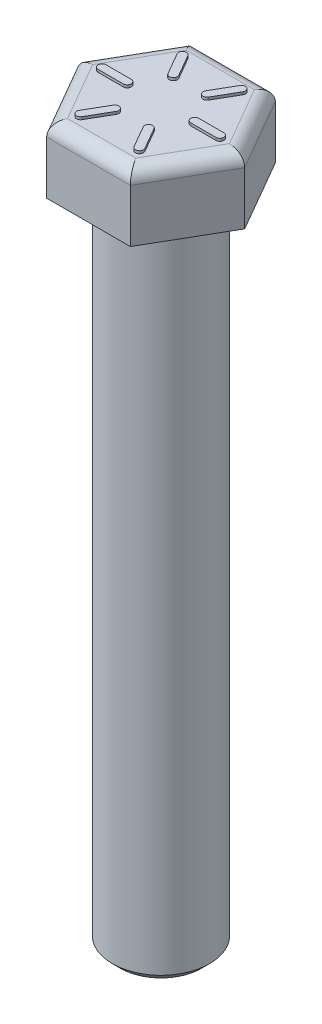
SolidWorks part; units mm, degrees
material "AISI 1045 Steel, cold drawn"
ref_plane "Front" through (0, 0, 0) normal (0, 0, 1) x (1, 0, 0)
ref_plane "Top" through (0, 0, 0) normal (0, 1, 0) x (1, 0, 0)
ref_plane "Right" through (0, 0, 0) normal (1, 0, 0) x (0, 0, -1)
sketch "Sketch1" plane through (0, 0, 0) normal (0, 1, 0) x (1, 0, 0)
  circle A0 centre (0, 0) radius 4.6609
  dimension "D1" = 9.3218
extrude "Boss-Extrude1" add sketch "Sketch1" against normal blind 63.5
cosmetic thread "Cosmetic Thread1" parameters "D1"=17.78, "D2"=6.2586
sketch "Sketch2" plane through (0, 0, 0) normal (0, 1, 0) x (1, 0, 0)
  line L1 (8.0289, 0) -> (4.0145, 6.9532)
  line L2 (4.0145, 6.9532) -> (-4.0145, 6.9532)
  line L3 (-4.0145, 6.9532) -> (-8.0289, 0)
  line L4 (-8.0289, 0) -> (-4.0145, -6.9532)
  line L5 (-4.0145, -6.9532) -> (4.0145, -6.9532)
  line L6 (4.0145, -6.9532) -> (8.0289, 0)
  circle A0 centre (0, 0) radius 6.9532 construction
  dimension "D1" = 13.9065
extrude "Boss-Extrude2" add sketch "Sketch2" along normal blind 6.35
fillet "Fillet1" radius 1.27 6 edges at (0, 6.35, 6.9532) (-6.0217, 6.35, 3.4766) (-6.0217, 6.35, -3.4766) (0, 6.35, -6.9532) (6.0217, 6.35, -3.4766) (6.0217, 6.35, 3.4766)
chamfer "Chamfer1" distance 0.762 angle 45 1 edges at (0, -63.5, 4.6609)
sketch "Sketch3" plane through (0, 6.35, 0) normal (0, 1, 0) x (1, 0, 0)
  line L0 (5.6515, 0) -> (3.2385, 0) construction
  line L1 (5.6515, -0.381) -> (3.2385, -0.381)
  line L2 (5.6515, 0.381) -> (3.2385, 0.381)
  line L3 (2.8258, 4.8943) -> (1.6193, 2.8046) construction
  line L4 (3.1557, 4.7038) -> (1.9492, 2.6141)
  line L5 (2.4958, 5.0848) -> (1.2893, 2.9951)
  line L6 (-2.8257, 4.8943) -> (-1.6192, 2.8046) construction
  line L7 (-2.4958, 5.0848) -> (-1.2893, 2.9951)
  line L8 (-3.1557, 4.7038) -> (-1.9492, 2.6141)
  line L9 (-5.6515, 0) -> (-3.2385, 0) construction
  line L10 (-5.6515, 0.381) -> (-3.2385, 0.381)
  line L11 (-5.6515, -0.381) -> (-3.2385, -0.381)
  line L12 (-2.8258, -4.8943) -> (-1.6193, -2.8046) construction
  line L13 (-3.1557, -4.7038) -> (-1.9492, -2.6141)
  line L14 (-2.4958, -5.0848) -> (-1.2893, -2.9951)
  line L15 (2.8258, -4.8943) -> (1.6192, -2.8046) construction
  line L16 (2.4958, -5.0848) -> (1.2893, -2.9951)
  line L17 (3.1557, -4.7038) -> (1.9492, -2.6141)
  arc A0 (5.6515, -0.381) -> (5.6515, 0.381) centre (5.6515, 0) ccw
  arc A1 (3.2385, 0.381) -> (3.2385, -0.381) centre (3.2385, 0) ccw
  circle A2 centre (0, 0) radius 2.8575 construction
  arc A3 (3.1557, 4.7038) -> (2.4958, 5.0848) centre (2.8258, 4.8943) ccw
  arc A4 (1.2893, 2.9951) -> (1.9492, 2.6141) centre (1.6193, 2.8046) ccw
  arc A5 (-2.4958, 5.0848) -> (-3.1557, 4.7038) centre (-2.8257, 4.8943) ccw
  arc A6 (-1.9492, 2.6141) -> (-1.2893, 2.9951) centre (-1.6192, 2.8046) ccw
  arc A7 (-5.6515, 0.381) -> (-5.6515, -0.381) centre (-5.6515, 0) ccw
  arc A8 (-3.2385, -0.381) -> (-3.2385, 0.381) centre (-3.2385, 0) ccw
  arc A9 (-3.1557, -4.7038) -> (-2.4958, -5.0848) centre (-2.8258, -4.8943) ccw
  arc A10 (-1.2893, -2.9951) -> (-1.9492, -2.6141) centre (-1.6193, -2.8046) ccw
  arc A11 (2.4958, -5.0848) -> (3.1557, -4.7038) centre (2.8258, -4.8943) ccw
  arc A12 (1.9492, -2.6141) -> (1.2893, -2.9951) centre (1.6192, -2.8046) ccw
  point P3 (4.445, 0)
  point P8 (6.0325, 0)
  point P9 (2.8575, 0)
  point P16 (2.2225, 3.8495)
  point P21 (3.0163, 5.2243)
  point P22 (1.4288, 2.4747)
  point P25 (-2.2225, 3.8495)
  point P30 (-3.0162, 5.2243)
  point P31 (-1.4287, 2.4747)
  point P34 (-4.445, 0)
  point P39 (-6.0325, 0)
  point P40 (-2.8575, 0)
  point P43 (-2.2225, -3.8495)
  point P48 (-3.0163, -5.2243)
  point P49 (-1.4288, -2.4747)
  point P52 (2.2225, -3.8495)
  point P57 (3.0163, -5.2243)
  point P58 (1.4288, -2.4747)
  point P59 (0, 0)
  dimension "D4" = 5.715
  dimension "D1" = 0.762
  dimension "D2" = 3.175
  dimension "D3" = 6.0325
  dimension "D5" = 6
extrude "Boss-Extrude3" add sketch "Sketch3" along normal blind 0.254
